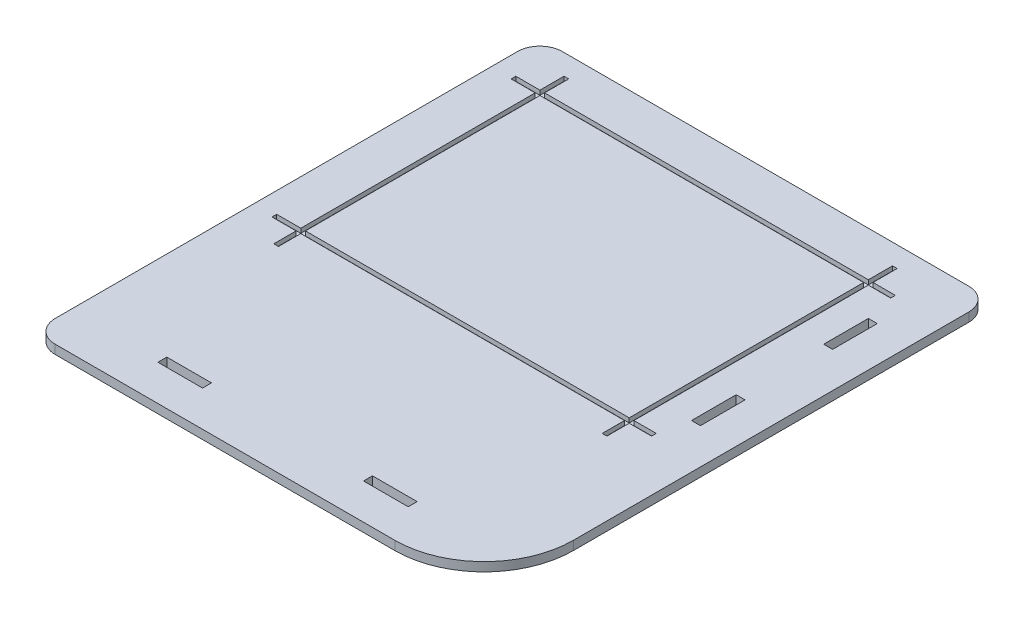
SolidWorks part; units mm, degrees
ref_plane "Front Plane" through (0, 0, 0) normal (0, 0, 1) x (1, 0, 0)
ref_plane "Top Plane" through (0, 0, 0) normal (0, 1, 0) x (1, 0, 0)
ref_plane "Right Plane" through (0, 0, 0) normal (1, 0, 0) x (0, 0, -1)
sketch "Sketch1" plane through (0, 0, 0) normal (0, 1, 0) x (1, 0, 0)
  line L0 (-2.1, -2.1) -> (147.1, -2.1) construction
  line L1 (0, 0) -> (145, 0) construction
  line L2 (0, 0) -> (0, 105) construction
  line L3 (0, 105) -> (145, 105) construction
  line L4 (145, 0) -> (145, 105) construction
  line L5 (147.1, -2.1) -> (147.1, 107.1) construction
  line L6 (-2.1, 107.1) -> (147.1, 107.1) construction
  line L7 (-2.1, -2.1) -> (-2.1, 107.1) construction
  line L9 (-12.1, 127.1) -> (170, 127.1)
  line L10 (-22.1, 117.1) -> (-22.1, -90)
  line L11 (-12.1, -100) -> (140, -100)
  line L12 (180, 117.1) -> (180, -60)
  line L13 (17.9, -80) -> (37.9, -80)
  line L14 (17.9, -80) -> (17.9, -84)
  line L15 (17.9, -84) -> (37.9, -84)
  line L16 (37.9, -80) -> (37.9, -84)
  line L17 (110, -80) -> (130, -80)
  line L18 (110, -80) -> (110, -84)
  line L19 (110, -84) -> (130, -84)
  line L20 (130, -80) -> (130, -84)
  line L21 (160, 92.1) -> (164, 92.1)
  line L22 (160, 92.1) -> (160, 72.1)
  line L23 (160, 72.1) -> (164, 72.1)
  line L24 (164, 92.1) -> (164, 72.1)
  line L25 (160, 32.9) -> (164, 32.9)
  line L26 (160, 32.9) -> (160, 12.9)
  line L27 (160, 12.9) -> (164, 12.9)
  line L28 (164, 32.9) -> (164, 12.9)
  arc A0 (140, -100) -> (180, -60) centre (140, -60) ccw
  arc A1 (-12.1, 127.1) -> (-22.1, 117.1) centre (-12.1, 117.1) ccw
  arc A2 (170, 127.1) -> (180, 117.1) centre (170, 117.1) cw
  arc A3 (-22.1, -90) -> (-12.1, -100) centre (-12.1, -90) ccw
  dimension "D16" = 40
  dimension "D17" = 10
  dimension "D1" = 145
  dimension "D2" = 105
  dimension "D4" = 20
  dimension "D5" = 20
  dimension "D6" = 35
  dimension "D7" = 100
  dimension "D8" = 4
  dimension "D9" = 80
  dimension "D10" = 20
  dimension "D11" = 40
  dimension "D12" = 50
  dimension "D13" = 35
  dimension "D14" = 30
  dimension "D15" = 15
  dimension "D3" = 2.1
extrude "Boss-Extrude1" add sketch "Sketch1" along normal blind 4
sketch "Sketch2" plane through (0, 4, 0) normal (0, 1, 0) x (1, 0, 0)
  line L0 (72.5, 105) -> (72.5, -48.6388) construction
  line L1 (-12.9, 0) -> (-2.1, 0)
  line L2 (-12.9, 0) -> (-12.9, -2.1)
  line L3 (-12.9, -2.1) -> (-2.1, -2.1)
  line L4 (157.1, 0) -> (157.1, -2.1)
  line L5 (147.1, 117.9) -> (145, 117.9)
  line L6 (147.1, 117.9) -> (147.1, 107.1)
  line L7 (147.1, -12.1) -> (145, -12.1)
  line L8 (145, 117.9) -> (145, 107.1)
  line L9 (0, 105) -> (145, 105) construction
  line L10 (-2.1, 52.5) -> (207.093, 52.5) construction
  line L11 (-2.1, -2.1) -> (-2.1, 107.1) construction
  line L12 (180, 117.1) -> (180, -60) construction
  line L13 (-12.1, -100) -> (140, -100) construction
  line L14 (157.1, 105) -> (157.1, 107.1)
  line L15 (-12.9, 105) -> (-12.9, 107.1)
  line L16 (-12.9, 107.1) -> (-2.1, 107.1)
  line L17 (-12.9, 105) -> (-2.1, 105)
  line L18 (0, 117.9) -> (0, 107.1)
  line L19 (-2.1, -12.1) -> (0, -12.1)
  line L20 (-2.1, 117.9) -> (-2.1, 107.1)
  line L21 (-2.1, 117.9) -> (0, 117.9)
  line L22 (0, -2.1) -> (145, -2.1)
  line L23 (-2.1, -2.1) -> (-2.1, -12.1)
  line L24 (0, 0) -> (145, 0)
  line L25 (0, -2.1) -> (0, -12.1)
  line L26 (145, -2.1) -> (145, -12.1)
  line L27 (147.1, 0) -> (157.1, 0)
  line L28 (147.1, -2.1) -> (147.1, -12.1)
  line L29 (147.1, -2.1) -> (157.1, -2.1)
  line L30 (147.1, 105) -> (157.1, 105)
  line L31 (145, 105) -> (145, 0)
  line L32 (147.1, 107.1) -> (157.1, 107.1)
  line L33 (147.1, 105) -> (147.1, 0)
  line L34 (-2.1, 105) -> (-2.1, 0)
  line L35 (0, 105) -> (145, 105)
  line L36 (0, 105) -> (0, 0)
  line L37 (0, 107.1) -> (145, 107.1)
  dimension "D1" = 10
  dimension "D2" = 10
  dimension "D3" = 170
  dimension "D4" = 2.1
  dimension "D5" = 2.1
  dimension "D6" = 32.9
  dimension "D7" = 97.9
  dimension "D8" = 130
extrude "Cut-Extrude1" cut sketch "Sketch2" against normal blind 2
sketch "Sketch3" plane through (0, 0, 80) normal (0, 0, 1) x (1, 0, 0)
  line L0 (-22.1, 4) -> (-22.1, 14)
  line L1 (-12.1, 24) -> (130, 24)
  line L2 (140, 14) -> (140, 4)
  line L3 (180, 4) -> (140, 4) construction
  line L4 (140, 4) -> (130, 4)
  line L5 (130, 4) -> (130, 0)
  line L6 (130, 0) -> (110, 0)
  line L7 (110, 0) -> (110, 4)
  line L8 (110, 4) -> (37.9, 4)
  line L9 (37.9, 4) -> (37.9, 0)
  line L10 (37.9, 0) -> (17.9, 0)
  line L11 (17.9, 0) -> (17.9, 4)
  line L12 (17.9, 4) -> (-22.1, 4)
  arc A0 (130, 24) -> (140, 14) centre (130, 14) cw
  arc A1 (-22.1, 14) -> (-12.1, 24) centre (-12.1, 14) cw
  dimension "D2" = 10
  dimension "D1" = 20
  dimension "D3" = 10
sketch "Sketch4" plane through (160, 0, 0) normal (1, 0, 0) x (0, 0, -1)
  line L0 (97.1, 14) -> (97.1, 4)
  line L1 (-60, 4) -> (117.1, 4) construction
  line L2 (97.1, 4) -> (92.1, 4)
  line L3 (92.1, 4) -> (92.1, 0)
  line L4 (92.1, 0) -> (72.1, 0)
  line L5 (72.1, 0) -> (72.1, 4)
  line L6 (72.1, 4) -> (32.9, 4)
  line L7 (32.9, 4) -> (32.9, 0)
  line L8 (32.9, 0) -> (13.55, 0)
  line L9 (117.1, 0) -> (-90, 0) construction
  line L10 (13.55, 0) -> (12.9, 0)
  line L11 (12.9, 0) -> (12.9, 4)
  line L12 (12.9, 4) -> (7.9, 4)
  line L13 (7.9, 4) -> (7.9, 14)
  line L14 (17.9, 24) -> (87.1, 24)
  arc A0 (97.1, 14) -> (87.1, 24) centre (87.1, 14) ccw
  arc A1 (7.9, 14) -> (17.9, 24) centre (17.9, 14) cw
  dimension "D4" = 10
  dimension "D1" = 20
  dimension "D2" = 5
  dimension "D3" = 5
